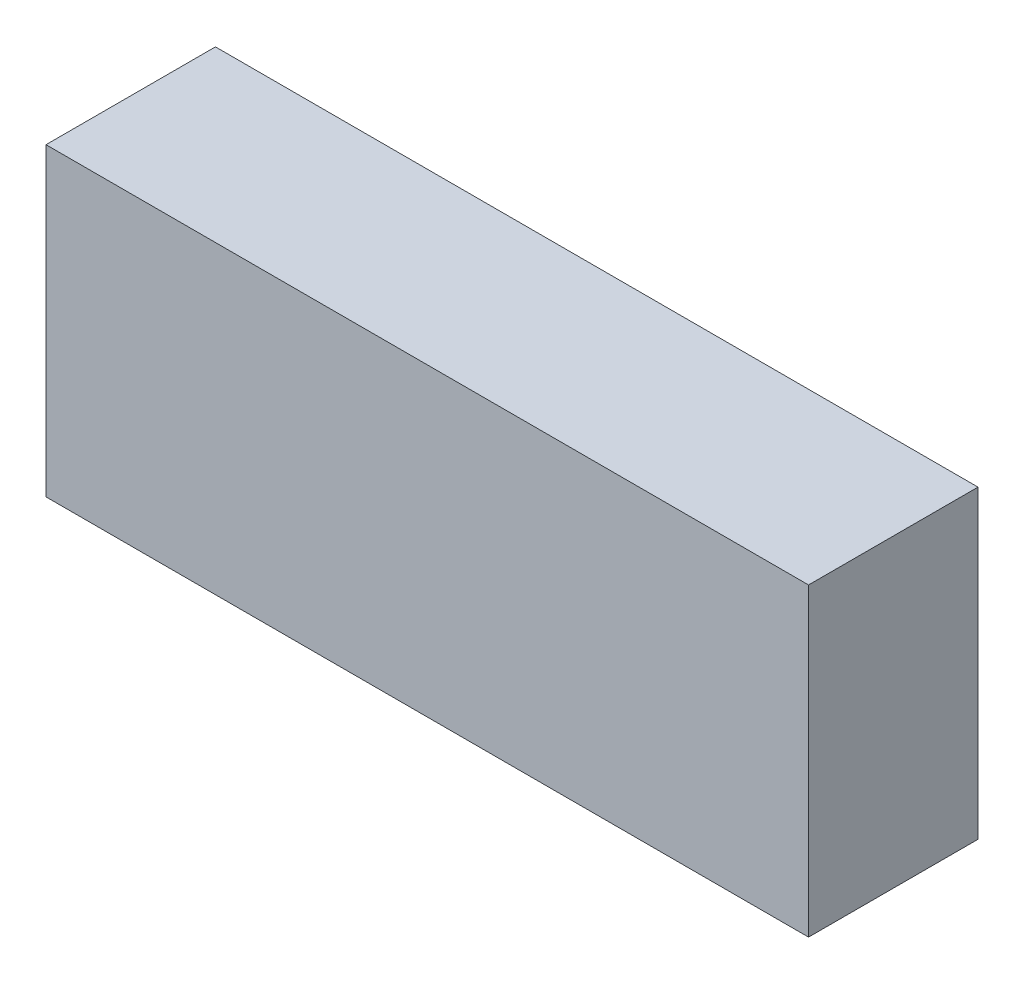
SolidWorks part; units mm, degrees
ref_plane "前视基准面" through (0, 0, 0) normal (0, 0, 1) x (1, 0, 0)
ref_plane "上视基准面" through (0, 0, 0) normal (0, 1, 0) x (1, 0, 0)
ref_plane "右视基准面" through (0, 0, 0) normal (1, 0, 0) x (0, 0, -1)
sketch "草图1" plane through (0, 0, 0) normal (0, 0, 1) x (1, 0, 0)
  line L1 (-29.221, 27.4368) -> (15.779, 27.4368)
  line L2 (-29.221, 27.4368) -> (-29.221, 9.4368)
  line L3 (-29.221, 9.4368) -> (15.779, 9.4368)
  line L4 (15.779, 27.4368) -> (15.779, 9.4368)
  dimension "D1" = 45
  dimension "D2" = 18
extrude "凸台-拉伸1" add sketch "草图1" along normal blind 10
